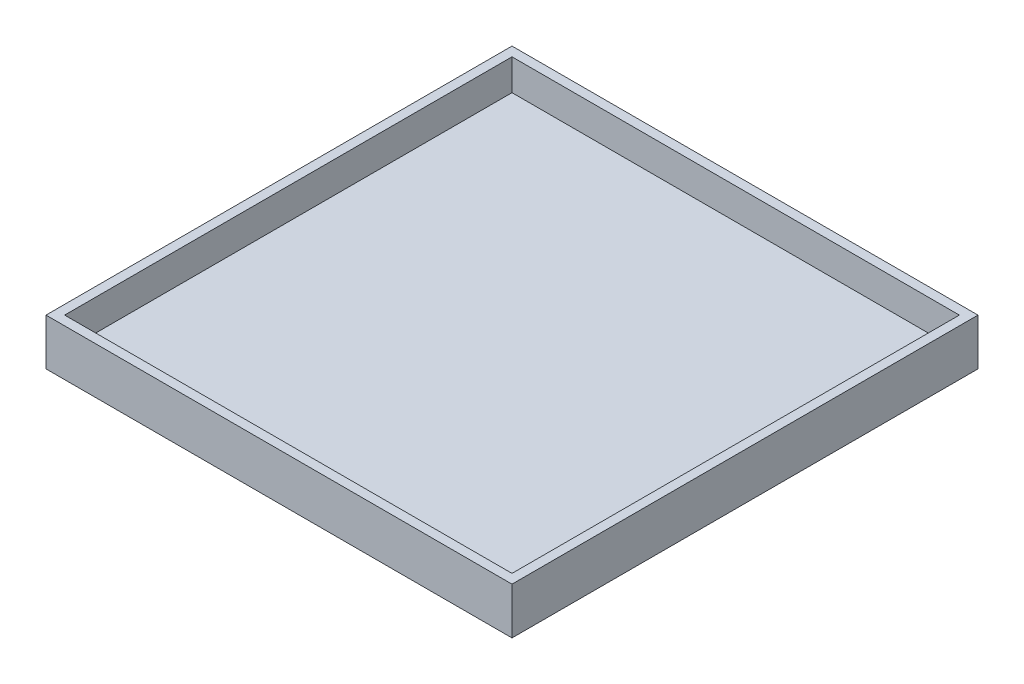
SolidWorks part; units mm, degrees
ref_plane "Front Plane" through (0, 0, 0) normal (0, 0, 1) x (1, 0, 0)
ref_plane "Top Plane" through (0, 0, 0) normal (0, 1, 0) x (1, 0, 0)
ref_plane "Right Plane" through (0, 0, 0) normal (1, 0, 0) x (0, 0, -1)
sketch "Sketch1" plane through (0, 0, 0) normal (0, 1, 0) x (1, 0, 0)
  line L1 (-75, -75) -> (75, -75)
  line L2 (-75, -75) -> (-75, 75)
  line L3 (-75, 75) -> (75, 75)
  line L4 (75, -75) -> (75, 75)
  line L5 (0, 75) -> (0, -75) construction
  line L6 (-75, 0) -> (75, 0) construction
  point P0 (0, 0)
  dimension "D1" = 150
extrude "Boss-Extrude1" add sketch "Sketch1" along normal blind 15
sketch "Sketch3" plane through (0, 15, 0) normal (0, 1, 0) x (1, 0, 0)
  line L0 (-72, 72) -> (-72, -72)
  line L1 (-75, 75) -> (-75, -75) construction
  line L6 (75, 75) -> (-75, 75) construction
  line L9 (-75, -75) -> (75, -75) construction
  line L10 (-72, 72) -> (72, 72)
  line L11 (75, -75) -> (75, 75) construction
  line L12 (72, 72) -> (72, -72)
  line L13 (72, -72) -> (-72, -72)
  dimension "D1" = 3
  dimension "D2" = 3
  dimension "D3" = 3
  dimension "D4" = 3
extrude "Cut-Extrude1" cut sketch "Sketch3" against normal blind 10
